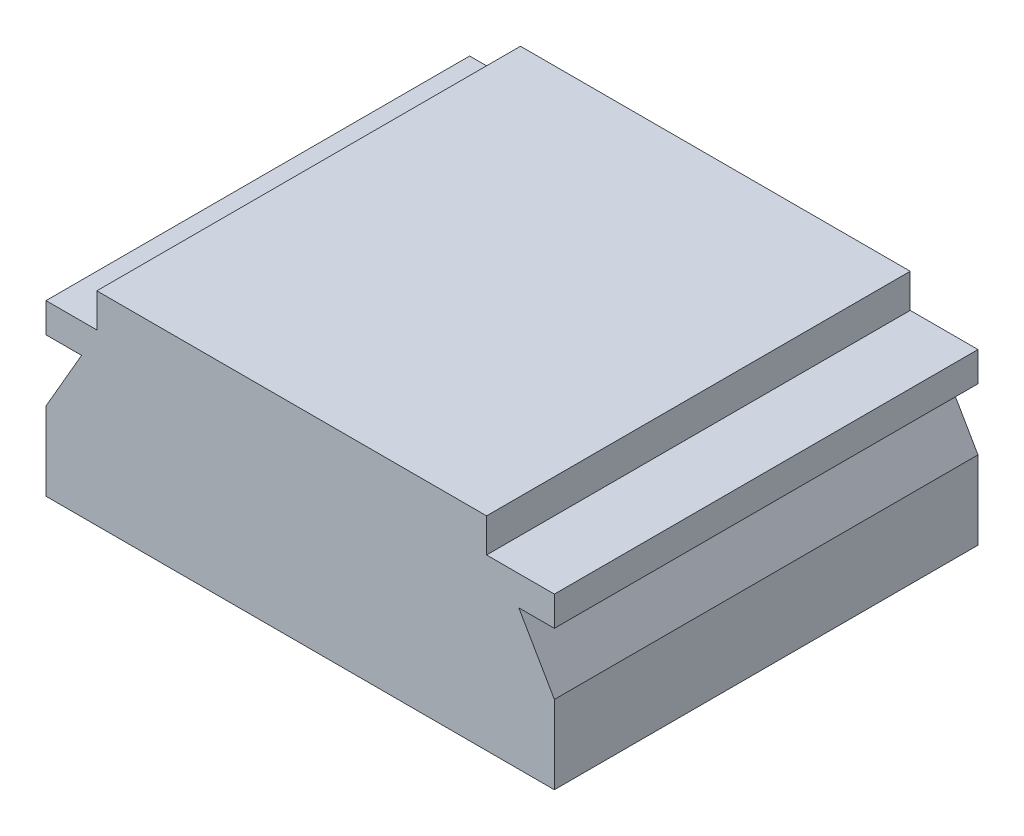
SolidWorks part; units mm, degrees
ref_plane "前视基准面" through (0, 0, 0) normal (0, 0, 1) x (1, 0, 0)
ref_plane "上视基准面" through (0, 0, 0) normal (0, 1, 0) x (1, 0, 0)
ref_plane "右视基准面" through (0, 0, 0) normal (1, 0, 0) x (0, 0, -1)
other "Configuration Table"
sketch "草图1" plane through (0, 0, 0) normal (0, 0, 1) x (1, 0, 0)
  line L1 (-6.2, 2.5) -> (6.2, 2.5)
  line L2 (-6.2, 2.5) -> (-6.2, -2.5)
  line L3 (-6.2, -2.5) -> (6.2, -2.5)
  line L4 (6.2, 2.5) -> (6.2, -2.5)
  line L5 (-6.2, 2.5) -> (6.2, -2.5) construction
  line L6 (-6.2, -2.5) -> (6.2, 2.5) construction
  point P0 (0, 0)
  dimension "D1" = 12.4
  dimension "D2" = 5
extrude "凸台-拉伸1" add sketch "草图1" along normal blind 10
sketch "草图2" plane through (0, 0, 0) normal (0, 0, -1) x (-1, 0, 0)
  line L37 (11.547, 2.7) -> (4.8, 2.7)
  line L38 (4.8, 2.7) -> (4.8, 1.7)
  line L39 (4.8, 1.7) -> (6, 1.7)
  line L40 (6, 1.7) -> (6, 1)
  line L41 (6, 1) -> (5.1608, 1)
  line L42 (5.1608, 1) -> (6, -0.4536)
  line L43 (6, -0.4536) -> (6, -2.3)
  line L44 (6, -2.3) -> (-6, -2.3)
  line L45 (-6, -2.3) -> (-6, -0.4536)
  line L46 (-6, -0.4536) -> (-5.1608, 1)
  line L47 (-5.1608, 1) -> (-6, 1)
  line L48 (-6, 1) -> (-6, 1.7)
  line L49 (-6, 1.7) -> (-4.4, 1.7)
  line L50 (-4.4, 1.7) -> (-4.4, 2.7)
  line L51 (-4.4, 2.7) -> (-11.547, 2.7)
  line L56 (-6.2, 2.5) -> (-6.2, -2.5)
  line L57 (-6.2, -2.5) -> (6.2, -2.5)
  line L58 (6.2, -2.5) -> (6.2, 2.5)
  line L59 (6.2, 2.5) -> (-6.2, 2.5)
  line L60 (-6.2, 2.5) -> (-6.2, -2.5)
  line L61 (-6.2, -2.5) -> (6.2, -2.5)
  line L62 (6.2, -2.5) -> (6.2, 2.5)
  line L63 (6.2, 2.5) -> (-6.2, 2.5)
  line L74 (6.2, -2.5) -> (-6.2, -2.5)
  line L75 (-6.2, -2.5) -> (-6.2, -0.4)
  line L76 (-6.2, -0.4) -> (-5.5072, 0.8)
  line L77 (-5.5072, 0.8) -> (-6.2, 0.8)
  line L78 (-6.2, 0.8) -> (-6.2, 1.9)
  line L79 (-6.2, 1.9) -> (-4.6, 1.9)
  line L80 (-4.6, 1.9) -> (-4.6, 2.5)
  line L81 (-4.6, 2.5) -> (-11.547, 2.5)
  line L104 (11.547, 2.5) -> (5, 2.5)
  line L105 (5, 2.5) -> (5, 1.9)
  line L106 (5, 1.9) -> (6.2, 1.9)
  line L107 (6.2, 1.9) -> (6.2, 0.8)
  line L108 (6.2, 0.8) -> (5.5072, 0.8)
  line L109 (5.5072, 0.8) -> (6.2, -0.4)
  line L110 (6.2, -0.4) -> (6.2, -2.5)
  line M42 (-6.2, 2.5) -> (-6.2, -2.5)
  line M43 (-6.2, -2.5) -> (6.2, -2.5)
  line M44 (6.2, -2.5) -> (6.2, 2.5)
  line M45 (6.2, 2.5) -> (-6.2, 2.5)
  dimension "D1" = 0.2
  dimension "D2" = 0
extrude "切除-拉伸1" cut sketch "草图2" against normal blind 10 contours L105 L106 L62 M45 | L109 L108 L62 L106 L105 L63 L38 L39 L40 L41 L42 L43 L44 L45 L46 L47 L48 L49 L50 L80 L79 L60 L77 L76 M45 M43 M44 | L108 L109 L62 | L76 L77 L60 | L79 L80 L63 M42
